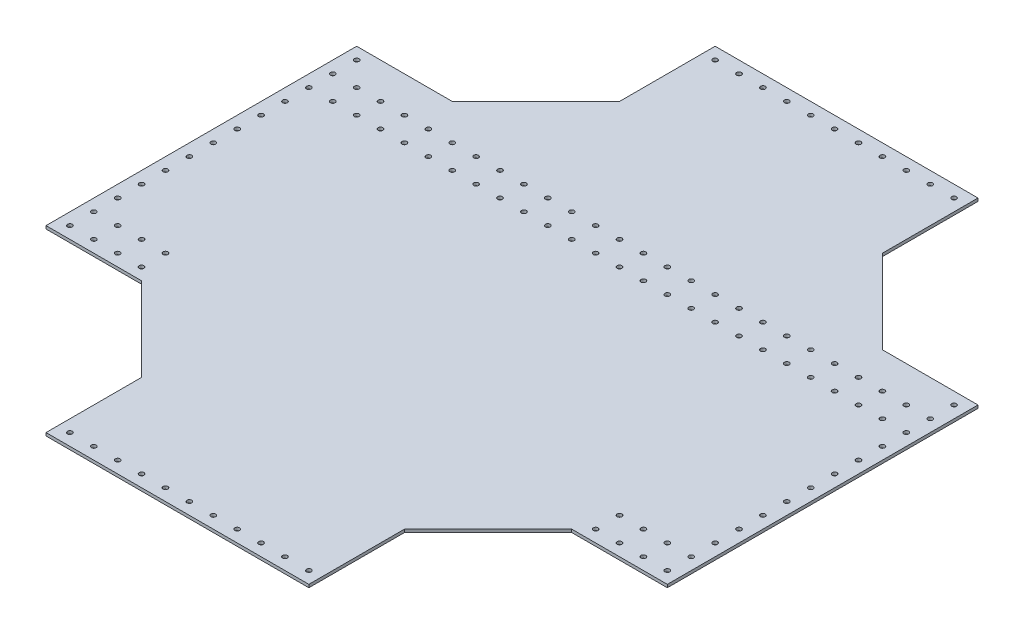
SolidWorks part; units mm, degrees
ref_plane "Front Plane" through (0, 0, 0) normal (0, 0, 1) x (1, 0, 0)
ref_plane "Top Plane" through (0, 0, 0) normal (0, 1, 0) x (1, 0, 0)
ref_plane "Right Plane" through (0, 0, 0) normal (1, 0, 0) x (0, 0, -1)
sketch "Sketch1" plane through (0, 0, 0) normal (0, 1, 0) x (1, 0, 0)
  line L0 (0, 0) -> (0, 101.6)
  line L1 (0, 101.6) -> (279.4, 101.6)
  line L2 (279.4, 101.6) -> (279.4, 0)
  line L3 (279.4, 0) -> (368.3045, -88.9045)
  line L4 (368.3045, -88.9045) -> (469.9045, -88.9045)
  line L5 (469.9045, -88.9045) -> (469.9045, -419.1045)
  line L6 (469.9045, -419.1045) -> (368.3045, -419.1045)
  line L7 (368.3045, -419.1045) -> (279.4, -508.0091)
  line L8 (279.4, -508.0091) -> (279.4, -609.6091)
  line L9 (279.4, -609.6091) -> (0, -609.6091)
  line L10 (0, -609.6091) -> (0, -508.0091)
  line L11 (0, -508.0091) -> (-88.9045, -419.1045)
  line L12 (-88.9045, -419.1045) -> (-190.5045, -419.1045)
  line L13 (-190.5045, -419.1045) -> (-190.5045, -88.9045)
  line L14 (-190.5045, -88.9045) -> (-88.9045, -88.9045)
  line L15 (-88.9045, -88.9045) -> (0, 0)
  line L16 (-190.5045, -88.9045) -> (-177.8045, -88.9045)
  line L17 (-177.8045, -88.9045) -> (-177.8045, -419.1045) construction
  line L18 (-177.8045, -419.1045) -> (-190.5045, -419.1045)
  line L19 (-177.8045, -101.6045) -> (-177.8045, -127.0045) construction
  line L20 (139.7, -898.4) -> (139.7, 49101.6) construction
  line L21 (-966.4523, 88.9) -> (49033.5477, 88.9) construction
  line L22 (12.7, 88.9) -> (38.1, 88.9) construction
  line L23 (-1190.5045, -254.0045) -> (48809.4955, -254.0045) construction
  line L24 (-190.5045, -368.3045) -> (-88.9045, -368.3045) construction
  line L25 (-88.9045, -368.3045) -> (-88.9045, -419.1045) construction
  line L26 (-101.6045, -406.4045) -> (-127.0045, -406.4045) construction
  line L27 (-101.6045, -381.0045) -> (-127.0045, -381.0045) construction
  line L28 (-1102.5698, -114.3045) -> (48897.4302, -114.3045) construction
  line L29 (-1089.6596, -165.1045) -> (48910.3404, -165.1045) construction
  line L30 (-177.8045, -127.0045) -> (-152.4045, -127.0045) construction
  circle A0 centre (-177.8045, -101.6045) radius 2.54
  circle A1 centre (-177.8045, -127.0045) radius 2.54
  circle A2 centre (-177.8045, -152.4045) radius 2.54
  circle A3 centre (-177.8045, -177.8045) radius 2.54
  circle A4 centre (-177.8045, -203.2045) radius 2.54
  circle A5 centre (-177.8045, -228.6045) radius 2.54
  circle A6 centre (-177.8045, -254.0045) radius 2.54
  circle A7 centre (-177.8045, -279.4045) radius 2.54
  circle A8 centre (-177.8045, -304.8045) radius 2.54
  circle A9 centre (-177.8045, -330.2045) radius 2.54
  circle A10 centre (-177.8045, -355.6045) radius 2.54
  circle A11 centre (-177.8045, -381.0045) radius 2.54
  circle A12 centre (-177.8045, -406.4045) radius 2.54
  circle A13 centre (457.2045, -406.4045) radius 2.54
  circle A14 centre (457.2045, -381.0045) radius 2.54
  circle A15 centre (457.2045, -355.6045) radius 2.54
  circle A16 centre (457.2045, -330.2045) radius 2.54
  circle A17 centre (457.2045, -304.8045) radius 2.54
  circle A18 centre (457.2045, -279.4045) radius 2.54
  circle A19 centre (457.2045, -254.0045) radius 2.54
  circle A20 centre (457.2045, -228.6045) radius 2.54
  circle A21 centre (457.2045, -152.4045) radius 2.54
  circle A22 centre (457.2045, -177.8045) radius 2.54
  circle A23 centre (457.2045, -203.2045) radius 2.54
  circle A24 centre (457.2045, -127.0045) radius 2.54
  circle A25 centre (457.2045, -101.6045) radius 2.54
  circle A26 centre (12.7, 88.9) radius 2.54
  circle A27 centre (38.1, 88.9) radius 2.54
  circle A28 centre (63.5, 88.9) radius 2.54
  circle A29 centre (88.9, 88.9) radius 2.54
  circle A30 centre (114.3, 88.9) radius 2.54
  circle A31 centre (139.7, 88.9) radius 2.54
  circle A32 centre (165.1, 88.9) radius 2.54
  circle A33 centre (190.5, 88.9) radius 2.54
  circle A34 centre (215.9, 88.9) radius 2.54
  circle A35 centre (241.3, 88.9) radius 2.54
  circle A36 centre (266.7, 88.9) radius 2.54
  circle A37 centre (266.7, -596.9091) radius 2.54
  circle A38 centre (241.3, -596.9091) radius 2.54
  circle A39 centre (215.9, -596.9091) radius 2.54
  circle A40 centre (190.5, -596.9091) radius 2.54
  circle A41 centre (165.1, -596.9091) radius 2.54
  circle A42 centre (139.7, -596.9091) radius 2.54
  circle A43 centre (114.3, -596.9091) radius 2.54
  circle A44 centre (88.9, -596.9091) radius 2.54
  circle A45 centre (63.5, -596.9091) radius 2.54
  circle A46 centre (38.1, -596.9091) radius 2.54
  circle A47 centre (12.7, -596.9091) radius 2.54
  circle A48 centre (-101.6045, -381.0045) radius 2.54
  circle A49 centre (-101.6045, -406.4045) radius 2.54
  circle A50 centre (381.0045, -406.4045) radius 2.54
  circle A51 centre (381.0045, -381.0045) radius 2.54
  circle A52 centre (-127.0045, -406.4045) radius 2.54
  circle A53 centre (-152.4045, -406.4045) radius 2.54
  circle A54 centre (-127.0045, -381.0045) radius 2.54
  circle A55 centre (-152.4045, -381.0045) radius 2.54
  circle A56 centre (431.8045, -381.0045) radius 2.54
  circle A57 centre (406.4045, -381.0045) radius 2.54
  circle A58 centre (431.8045, -406.4045) radius 2.54
  circle A59 centre (406.4045, -406.4045) radius 2.54
  circle A60 centre (-152.4045, -127.0045) radius 2.54
  circle A61 centre (-152.4045, -152.4045) radius 2.54
  circle A62 centre (-127.0045, -127.0045) radius 2.54
  circle A63 centre (-127.0045, -152.4045) radius 2.54
  circle A64 centre (-101.6045, -127.0045) radius 2.54
  circle A65 centre (-101.6045, -152.4045) radius 2.54
  circle A66 centre (-76.2045, -127.0045) radius 2.54
  circle A67 centre (-76.2045, -152.4045) radius 2.54
  circle A68 centre (-50.8045, -127.0045) radius 2.54
  circle A69 centre (-50.8045, -152.4045) radius 2.54
  circle A70 centre (-25.4045, -127.0045) radius 2.54
  circle A71 centre (-25.4045, -152.4045) radius 2.54
  circle A72 centre (-0.0045, -127.0045) radius 2.54
  circle A73 centre (-0.0045, -152.4045) radius 2.54
  circle A74 centre (25.3955, -127.0045) radius 2.54
  circle A75 centre (25.3955, -152.4045) radius 2.54
  circle A76 centre (50.7955, -127.0045) radius 2.54
  circle A77 centre (50.7955, -152.4045) radius 2.54
  circle A78 centre (76.1955, -127.0045) radius 2.54
  circle A79 centre (76.1955, -152.4045) radius 2.54
  circle A80 centre (101.5955, -127.0045) radius 2.54
  circle A81 centre (101.5955, -152.4045) radius 2.54
  circle A82 centre (126.9955, -127.0045) radius 2.54
  circle A83 centre (126.9955, -152.4045) radius 2.54
  circle A84 centre (152.3955, -127.0045) radius 2.54
  circle A85 centre (152.3955, -152.4045) radius 2.54
  circle A86 centre (177.7955, -127.0045) radius 2.54
  circle A87 centre (177.7955, -152.4045) radius 2.54
  circle A88 centre (203.1955, -127.0045) radius 2.54
  circle A89 centre (203.1955, -152.4045) radius 2.54
  circle A90 centre (228.5955, -127.0045) radius 2.54
  circle A91 centre (228.5955, -152.4045) radius 2.54
  circle A92 centre (253.9955, -127.0045) radius 2.54
  circle A93 centre (253.9955, -152.4045) radius 2.54
  circle A94 centre (279.3955, -127.0045) radius 2.54
  circle A95 centre (279.3955, -152.4045) radius 2.54
  circle A96 centre (304.7955, -127.0045) radius 2.54
  circle A97 centre (304.7955, -152.4045) radius 2.54
  circle A98 centre (330.1955, -127.0045) radius 2.54
  circle A99 centre (330.1955, -152.4045) radius 2.54
  circle A100 centre (355.5955, -127.0045) radius 2.54
  circle A101 centre (355.5955, -152.4045) radius 2.54
  circle A102 centre (380.9955, -127.0045) radius 2.54
  circle A103 centre (380.9955, -152.4045) radius 2.54
  circle A104 centre (406.3955, -127.0045) radius 2.54
  circle A105 centre (406.3955, -152.4045) radius 2.54
  circle A106 centre (431.7955, -127.0045) radius 2.54
  circle A107 centre (431.7955, -152.4045) radius 2.54
  point P50 (139.7, 101.6)
  point P105 (-190.5045, -254.0045)
  dimension "D11" = 5.08
  dimension "D16" = 5.08
  dimension "D21" = 5.08
  dimension "D22" = 5.08
  dimension "D1" = 135
  dimension "D2" = 135
  dimension "D3" = 135
  dimension "D4" = 135
  dimension "D5" = 101.6
  dimension "D6" = 279.4
  dimension "D7" = 330.2
  dimension "D8" = 101.6
  dimension "D9" = 125.73
  dimension "D10" = 12.7
  dimension "D12" = 12.7
  dimension "D13" = 25.4
  dimension "D15" = 12.7
  dimension "D17" = 12.7
  dimension "D18" = 25.4
  dimension "D19" = 101.6
  dimension "D20" = 50.8
  dimension "D23" = 12.7
  dimension "D24" = 12.7
  dimension "D25" = 12.7
  dimension "D26" = 12.7
  dimension "D27" = 25.4
  dimension "D28" = 25.4
  dimension "D29" = 25.4
  dimension "D30" = 50.8
  dimension "D31" = 25.4
  dimension "D14" = 13
extrude "Boss-Extrude1" add sketch "Sketch1" along normal blind 3.175 contours L15 L14 L13 L12 L11 L10 L9 L8 L7 L6 L5 L4 L3 L2 L1 L0 A107 A106 A105 A104 A103 A102 A101 A100 A99 A98 A97 A96 A95 A94 A93 A92
